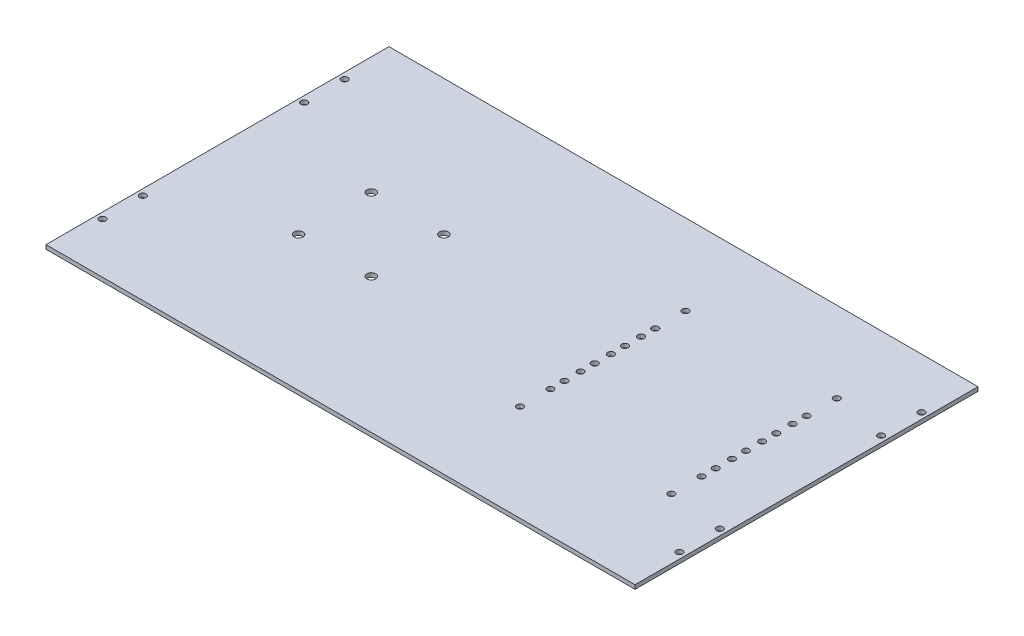
SolidWorks part; units mm, degrees
material "Thornel Mat VMA"
ref_plane "前视基准面" through (0, 0, 0) normal (0, 0, 1) x (1, 0, 0)
ref_plane "上视基准面" through (0, 0, 0) normal (0, 1, 0) x (1, 0, 0)
ref_plane "右视基准面" through (0, 0, 0) normal (1, 0, 0) x (0, 0, -1)
sketch "草图1" plane through (0, 0, 0) normal (0, 1, 0) x (1, 0, 0)
  line L0 (3, 45) -> (3, 25) construction
  line L1 (0, 0) -> (292, 0)
  line L2 (0, 0) -> (0, 170)
  line L3 (0, 170) -> (292, 170)
  line L4 (292, 0) -> (292, 170)
  line L5 (3, 145) -> (3, 125) construction
  line L7 (289, 45) -> (289, 25) construction
  line L8 (289, 145) -> (289, 125) construction
  line L9 (0, 85) -> (58.2249, 85) construction
  line L14 (58.2249, 103) -> (58.2249, 85) construction
  line L21 (58.2249, 103) -> (94.2249, 103) construction
  line L22 (58.2249, 67) -> (94.2249, 67) construction
  line L23 (94.2249, 67) -> (94.2249, 103) construction
  line L25 (58.2249, 85) -> (58.2249, 67) construction
  circle A0 centre (3, 145) radius 1.6
  circle A1 centre (3, 125) radius 1.6
  circle A2 centre (3, 45) radius 1.6
  circle A3 centre (3, 25) radius 1.6
  circle A4 centre (289, 25) radius 1.6
  circle A5 centre (289, 45) radius 1.6
  circle A6 centre (289, 125) radius 1.6
  circle A7 centre (289, 145) radius 1.6
  circle A8 centre (187, 130) radius 1.6
  circle A9 centre (262, 130) radius 1.6
  circle A10 centre (262, 108) radius 1.6
  circle A11 centre (187, 108) radius 1.6
  circle A12 centre (187, 115) radius 1.6
  circle A13 centre (262, 115) radius 1.6
  circle A14 centre (187, 93) radius 1.6
  circle A15 centre (262, 93) radius 1.6
  circle A16 centre (187, 100) radius 1.6
  circle A17 centre (262, 100) radius 1.6
  circle A18 centre (187, 78) radius 1.6
  circle A19 centre (262, 78) radius 1.6
  circle A20 centre (187, 85) radius 1.6
  circle A21 centre (262, 85) radius 1.6
  circle A22 centre (187, 63) radius 1.6
  circle A23 centre (262, 63) radius 1.6
  circle A24 centre (187, 70) radius 1.6
  circle A25 centre (262, 70) radius 1.6
  circle A26 centre (187, 48) radius 1.6
  circle A27 centre (262, 48) radius 1.6
  circle A28 centre (58.2249, 103) radius 2.2
  circle A29 centre (94.2249, 103) radius 2.2
  circle A30 centre (94.2249, 67) radius 2.2
  circle A31 centre (58.2249, 67) radius 2.2
  dimension "D3" = 20
  dimension "D5" = 3.2
  dimension "D7" = 25
  dimension "D14" = 3.2
  dimension "D9" = 18
  dimension "D1" = 292
  dimension "D2" = 170
  dimension "D4" = 3
  dimension "D6" = 25
  dimension "D8" = 20
  dimension "D10" = 18
  dimension "D11" = 36
  dimension "D12" = 22
  dimension "D13" = 75
  dimension "D19" = 36
  dimension "D17" = 5
extrude "凸台-拉伸1" add sketch "草图1" along normal blind 2
sketch "草图2" plane through (0, 2, 0) normal (0, 1, 0) x (1, 0, 0)
  line L0 (94.2249, 67) -> (58.2249, 103)
  line L1 (58.2249, 103) -> (58.2249, 67)
  line L2 (58.2249, 67) -> (94.2249, 103)
  line L3 (94.2249, 103) -> (58.2249, 103)
  line L4 (94.2249, 103) -> (94.2249, 67)
  line L5 (58.2249, 67) -> (94.2249, 67)
  line L6 (76.2249, 85) -> (76.2249, 67)
  point P8 (76.2249, 85)
ref_point "点1"
